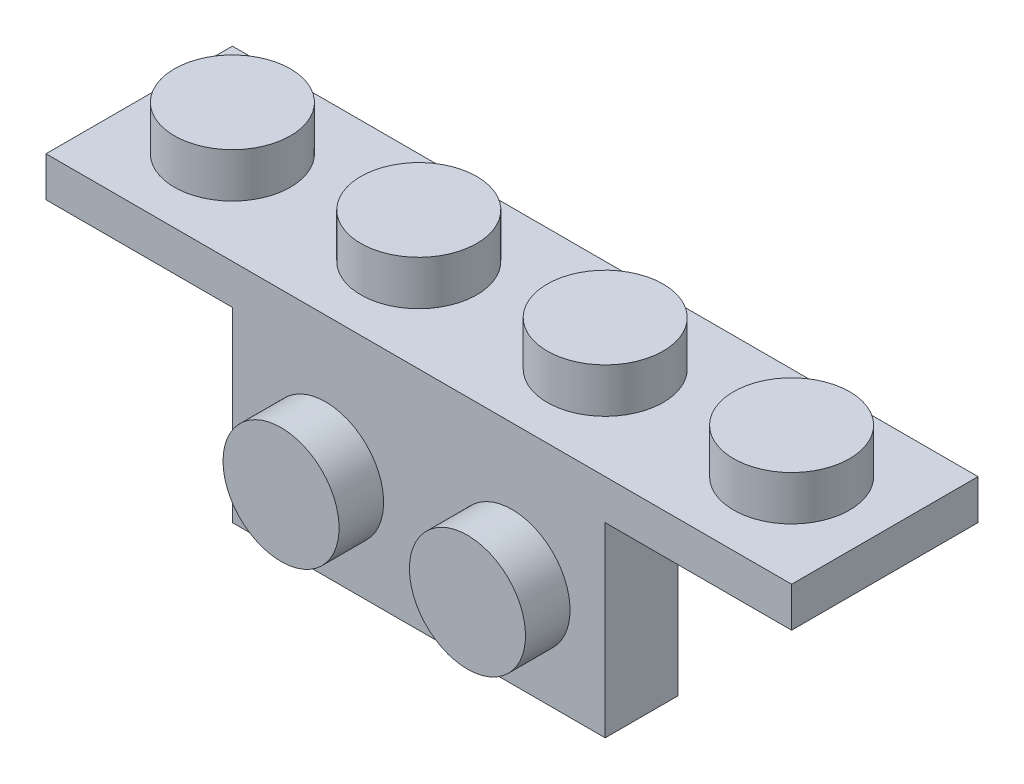
SolidWorks part; units mm, degrees
ref_plane "Front Plane" through (0, 0, 0) normal (0, 0, 1) x (1, 0, 0)
ref_plane "Top Plane" through (0, 0, 0) normal (0, 1, 0) x (1, 0, 0)
ref_plane "Right Plane" through (0, 0, 0) normal (1, 0, 0) x (0, 0, -1)
sketch "Sketch1" plane through (0, 0, 0) normal (0, 0, 1) x (1, 0, 0)
  line L1 (0, 0) -> (15.9, 0)
  line L2 (0, 0) -> (0, -7.95)
  line L3 (0, -7.95) -> (15.9, -7.95)
  line L4 (15.9, 0) -> (15.9, -7.95)
  dimension "D1" = 15.9
  dimension "D2" = 7.95
extrude "Boss-Extrude1" add sketch "Sketch1" along normal blind 3.1
sketch "Sketch2" plane through (0, 0, 3.1) normal (0, 0, 1) x (1, 0, 0)
  line L0 (0, 0) -> (0, -7.95) construction
  line L1 (15.9, -7.95) -> (15.9, 0) construction
  line L2 (0, -7.95) -> (15.9, -7.95) construction
  line L4 (15.9, 0) -> (0, 0) construction
  circle A0 centre (3.975, -3.975) radius 2.475
  circle A1 centre (11.925, -3.975) radius 2.475
  point P6 (15.9, -3.975)
  dimension "D1" = 4.95
  dimension "D2" = 4.95
  dimension "D3" = 3.975
  dimension "D4" = 3.975
  dimension "D5" = 3.975
  dimension "D6" = 3.975
  dimension "D7" = 3.975
  dimension "D8" = 7.95
extrude "Boss-Extrude2" add sketch "Sketch2" along normal blind 1.9
sketch "Sketch3" plane through (0, 0, 0) normal (0, 0, -1) x (-1, 0, 0)
  line L0 (-15.9, 0) -> (0, 0) construction
  line L1 (-14.4, -1.5) -> (-1.5, -1.5)
  line L2 (-14.4, -1.5) -> (-14.4, -6.45)
  line L3 (-14.4, -6.45) -> (-1.5, -6.45)
  line L4 (-1.5, -1.5) -> (-1.5, -6.45)
  line L5 (-15.9, -7.95) -> (-15.9, 0) construction
  line L6 (0, -7.95) -> (-15.9, -7.95) construction
  line L7 (0, 0) -> (0, -7.95) construction
  dimension "D1" = 1.5
  dimension "D2" = 1.5
  dimension "D3" = 1.5
  dimension "D4" = 1.5
extrude "Cut-Extrude1" cut sketch "Sketch3" against normal blind 2
sketch "Sketch4" plane through (0, 0, 0) normal (0, 1, 0) x (1, 0, 0)
  line L0 (1.5, -3.1) -> (6.45, -3.1) construction
  line L1 (-7.95, 4.85) -> (23.85, 4.85)
  line L2 (-7.95, 4.85) -> (-7.95, -3.1)
  line L3 (-7.95, -3.1) -> (23.85, -3.1)
  line L4 (23.85, 4.85) -> (23.85, -3.1)
  line L5 (0, 0) -> (15.9, 0) construction
  point P9 (7.95, 0)
  dimension "D1" = 0
  dimension "D2" = 7.95
  dimension "D3" = 31.8
  dimension "D4" = 15.9
extrude "Boss-Extrude3" add sketch "Sketch4" along normal blind 1.7
sketch "Sketch5" plane through (0, 1.7, 0) normal (0, 1, 0) x (1, 0, 0)
  line L0 (23.85, 4.85) -> (-7.95, 4.85) construction
  line L5 (-7.95, 4.85) -> (-7.95, -3.1) construction
  circle A0 centre (-3.975, 0.875) radius 2.475
  point P14 (-7.95, 0.875)
  dimension "D1" = 3.975
  dimension "D2" = 4.95
  dimension "D3" = 3.975
extrude "Boss-Extrude4" add sketch "Sketch5" along normal blind 1.9
pattern_linear "LPattern1" count 4 spacing 7.95 along (1, 0, 0) of "Boss-Extrude4"
